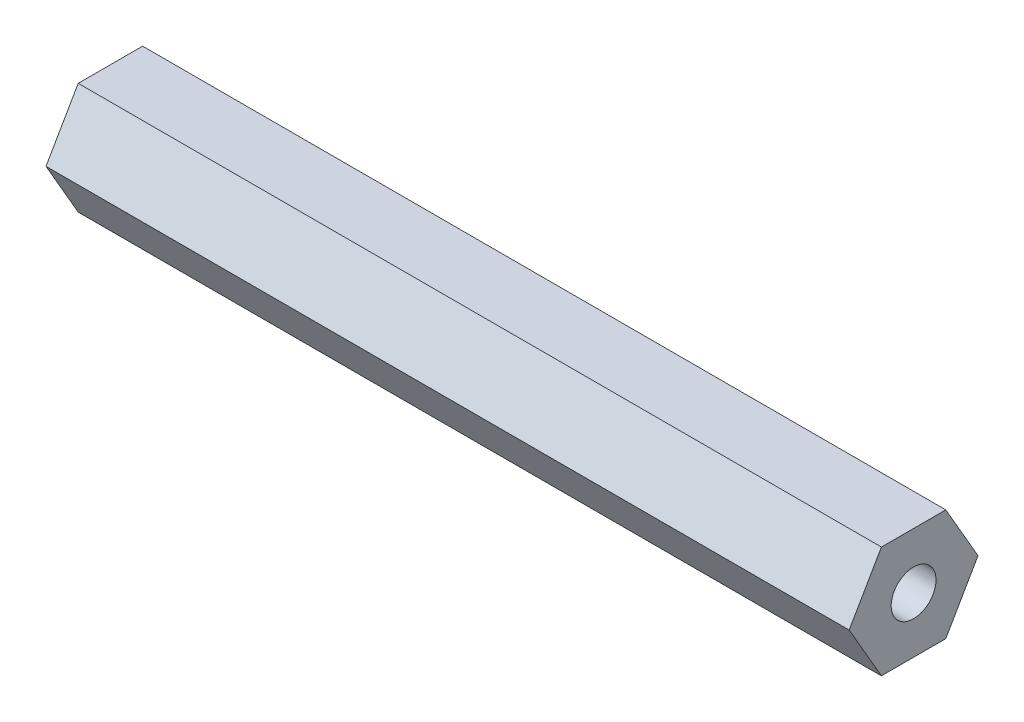
SolidWorks part; units mm, degrees
ref_plane "Front Plane" through (0, 0, 0) normal (0, 0, 1) x (1, 0, 0)
ref_plane "Top Plane" through (0, 0, 0) normal (0, 1, 0) x (1, 0, 0)
ref_plane "Right Plane" through (0, 0, 0) normal (1, 0, 0) x (0, 0, -1)
sketch "Sketch1" plane through (0, 0, 0) normal (1, 0, 0) x (0, 0, -1)
  line L1 (7.3323, 0) -> (3.6662, 6.35)
  line L2 (3.6662, 6.35) -> (-3.6662, 6.35)
  line L3 (-3.6662, 6.35) -> (-7.3323, 0)
  line L4 (-7.3323, 0) -> (-3.6662, -6.35)
  line L5 (-3.6662, -6.35) -> (3.6662, -6.35)
  line L6 (3.6662, -6.35) -> (7.3323, 0)
  circle A0 centre (0, 0) radius 6.35 construction
  point P1 (7.3323, 0)
  dimension "D1" = 12.7
extrude "Boss-Extrude1" add sketch "Sketch1" along normal blind 91.44
hole_wizard "Tap Drill for 1/4-20 Tap1" positions "Sketch2" profile "Sketch3" hole size "1/4-20" standard "ANSI Inch"
sketch "Sketch2" plane through (0, 0, 0) normal (-1, 0, 0) x (0, 0, 1)
  point P0 (0, 0)
sketch "Sketch3" plane through (0, 0, 0) normal (0, 1, 0) x (0, 0, 1)
  line L0 (0, 0) -> (0, 14.2338)
  line L1 (0, 14.2338) -> (2.5527, 12.7)
  line L2 (2.5527, 12.7) -> (2.5527, 0)
  line L5 (2.5527, 0) -> (0, 0)
  line L10 (0, 14.2338) -> (-2.5527, 12.7) construction
  line L11 (0, -6.35) -> (0, 107.95) construction
  dimension "Hole Dia." = 5.1054
  dimension "Hole Depth" = 12.7
  dimension "Drill Angle" = 118
ref_plane "Plane1" through (45.72, 0, 0) normal (-1, 0, 0) x (0, 0, 1)
mirror "Mirror1" about plane through (45.72, 0, 0) normal (-1, 0, 0) of "Tap Drill for 1/4-20 Tap1"
